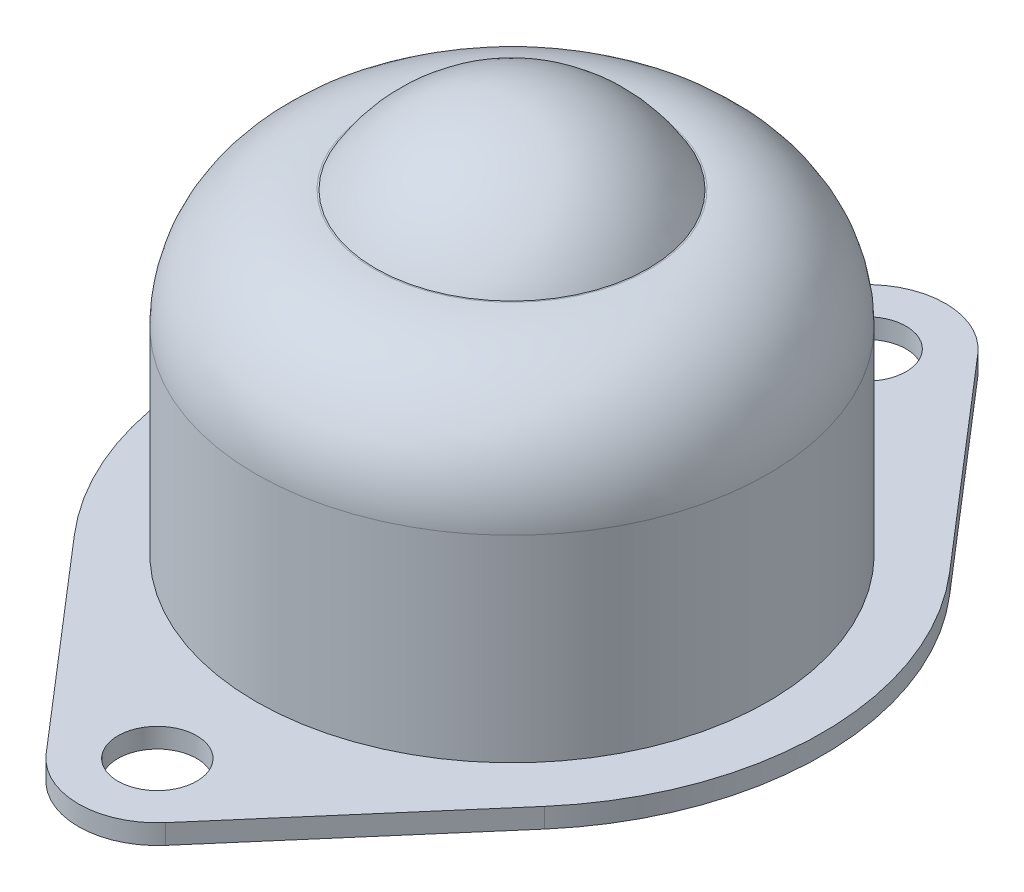
SolidWorks part; units mm, degrees
ref_plane "Front" through (0, 0, 0) normal (0, 0, 1) x (1, 0, 0)
ref_plane "Top" through (0, 0, 0) normal (0, 1, 0) x (1, 0, 0)
ref_plane "Right" through (0, 0, 0) normal (1, 0, 0) x (0, 0, -1)
sketch "Sketch1" plane through (0, 0, 0) normal (0, 1, 0) x (1, 0, 0)
  line L0 (0, 28.575) -> (0, -28.575) construction
  line L1 (4.811, -32.7194) -> (18.9411, -16.3167)
  line L2 (-4.811, -32.7194) -> (-18.9411, -16.3167)
  line L3 (-20.6375, 0) -> (25, 0) construction
  line L4 (4.811, 32.7194) -> (18.9411, 16.3167)
  line L5 (-4.811, 32.7194) -> (-18.9411, 16.3167)
  circle A1 centre (0, -28.575) radius 6.35
  circle A2 centre (0, -28.575) radius 3.175
  circle A3 centre (0, 0) radius 25
  circle A4 centre (0, 28.575) radius 3.175
  circle A5 centre (0, 28.575) radius 6.35
  dimension "D2" = 6.35
  dimension "D3" = 12.7
  dimension "D4" = 50
  dimension "D5" = 57.15
extrude "Boss-Extrude1" add sketch "Sketch1" along normal blind 1.5875 contours A3 A5 A1 | L4 A5 A3 | A5 A3 A4 | A3 A5 L5 | A3 A1 A2 | A3 A1 L1 | A3 L2 A1 | A1 A3 | A5 A3
sketch "Sketch2" plane through (0, 1.5875, 0) normal (0, 1, 0) x (1, 0, 0)
  circle A0 centre (0, 0) radius 20.6375
  dimension "D1" = 41.275
extrude "Boss-Extrude2" add sketch "Sketch2" along normal blind 25.4
fillet "Fillet1" radius 9.525 1 edges at (0, 26.9875, 20.6375)
sketch "Sketch4" plane through (0, 0, 0) normal (1, 0, 0) x (0, 0, -1)
  line L0 (0, 26.9875) -> (0, 33.3375)
  line L1 (0, 26.9875) -> (14.4703, 26.9875) construction
  line L2 (10.9985, 26.9875) -> (0, 26.9875)
  line L3 (11.1125, 26.9875) -> (-11.1125, 26.9875) construction
  line L5 (11.1125, 26.9875) -> (-11.1125, 26.9875) construction
  arc A0 (10.9985, 26.9875) -> (0, 33.3375) centre (0, 20.6375) ccw
  dimension "D1" = 25.4
  dimension "D2" = 6.35
revolve "Revolve1" add sketch "Sketch4" angle 360 about L0
